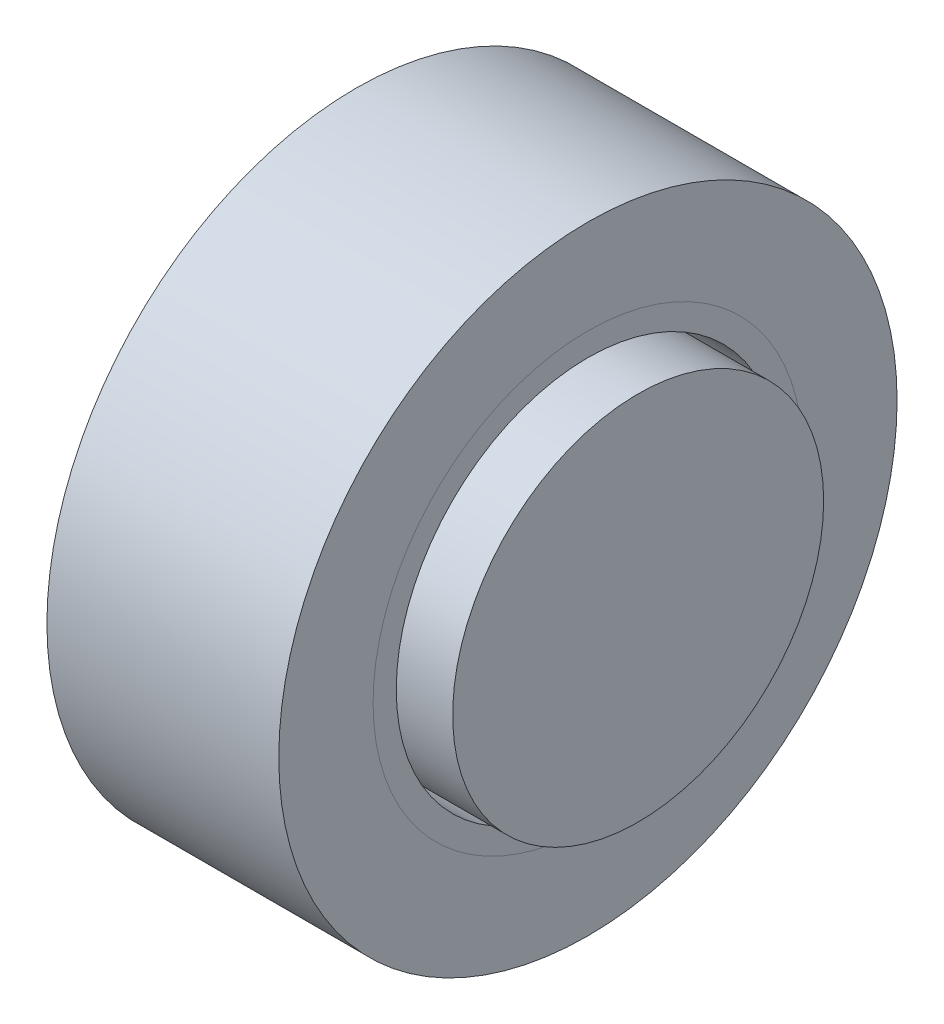
SolidWorks part; units mm, degrees
ref_plane "Front Plane" through (0, 0, 0) normal (0, 0, 1) x (1, 0, 0)
ref_plane "Top Plane" through (0, 0, 0) normal (0, 1, 0) x (1, 0, 0)
ref_plane "Right Plane" through (0, 0, 0) normal (1, 0, 0) x (0, 0, -1)
sketch "Sketch1" plane through (0, 0, 0) normal (1, 0, 0) x (0, 0, -1)
  circle A0 centre (0, 0) radius 27.8
extrude "CupFloor" add sketch "Sketch1" along normal blind 4.5 separate body
sketch "Sketch2" plane through (0, 0, 0) normal (1, 0, 0) x (0, 0, -1)
  circle A0 centre (0, 0) radius 27.8
  circle A1 centre (0, 0) radius 24.8
extrude "CupWall" add sketch "Sketch2" along normal blind 25.5 from offset 4.5 separate body
sketch "Sketch3" plane through (0, 0, 0) normal (1, 0, 0) x (0, 0, -1)
  circle A0 centre (0, 0) radius 24
extrude "Motor" add sketch "Sketch3" along normal blind 32 from offset 4.5 separate body
sketch "Sketch4" plane through (0, 0, 0) normal (1, 0, 0) x (0, 0, -1)
  circle A0 centre (0, 0) radius 40
  circle A1 centre (0, 0) radius 27.8
extrude "Foam" add sketch "Sketch4" along normal blind 30 separate body
